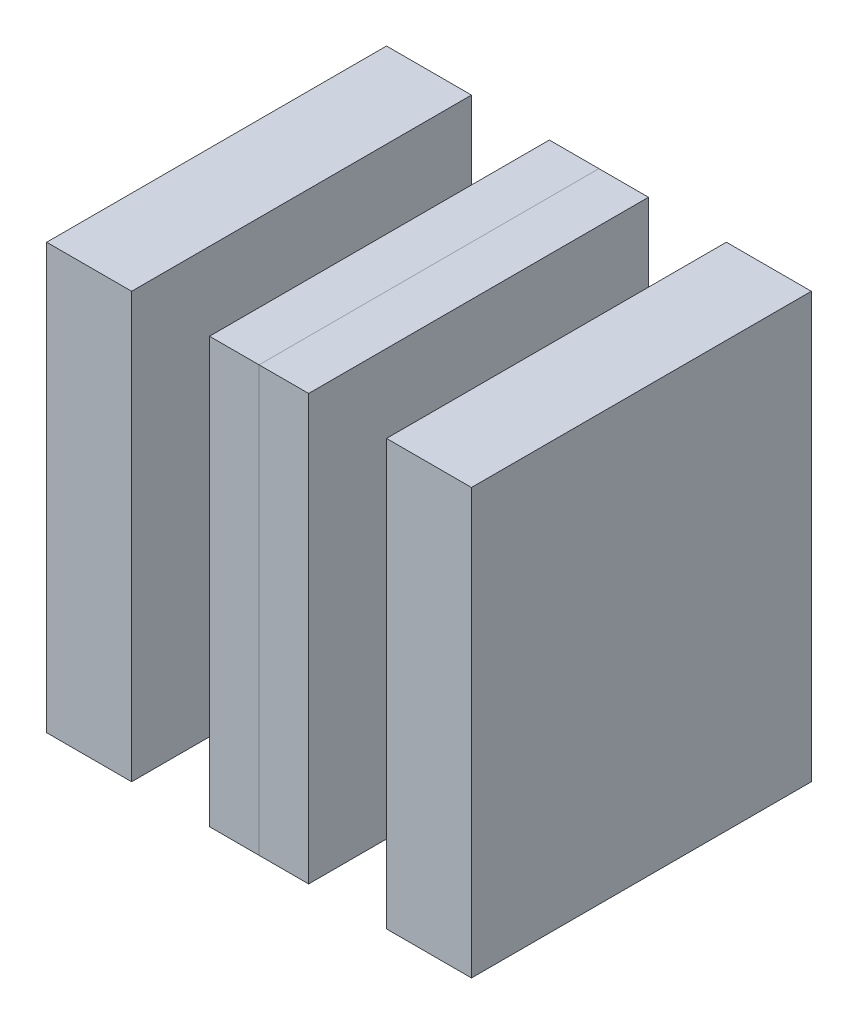
SolidWorks part; units mm, degrees
ref_plane "Front Plane" through (0, 0, 0) normal (0, 0, 1) x (1, 0, 0)
ref_plane "Top Plane" through (0, 0, 0) normal (0, 1, 0) x (1, 0, 0)
ref_plane "Right Plane" through (0, 0, 0) normal (1, 0, 0) x (0, 0, -1)
sketch "Sketch1" plane through (0, 0, 0) normal (0, 0, 1) x (1, 0, 0)
  line L1 (0, 0) -> (3, 0)
  line L2 (0, 0) -> (0, 15)
  line L3 (0, 15) -> (3, 15)
  line L4 (3, 0) -> (3, 15)
  line L5 (5.75, 15) -> (7.5, 15)
  line L6 (5.75, 15) -> (5.75, 0)
  line L7 (5.75, 0) -> (7.5, 0)
  line L8 (7.5, 15) -> (7.5, 0)
  dimension "D1" = 15
  dimension "D2" = 1.75
  dimension "D3" = 4.5
  dimension "D4" = 7.5
extrude "Boss-Extrude1" add sketch "Sketch1" along normal blind 12
mirror "Mirror1" about plane through (7.5, 15, 12) normal (-1, 0, 0) of bodies 102 101
